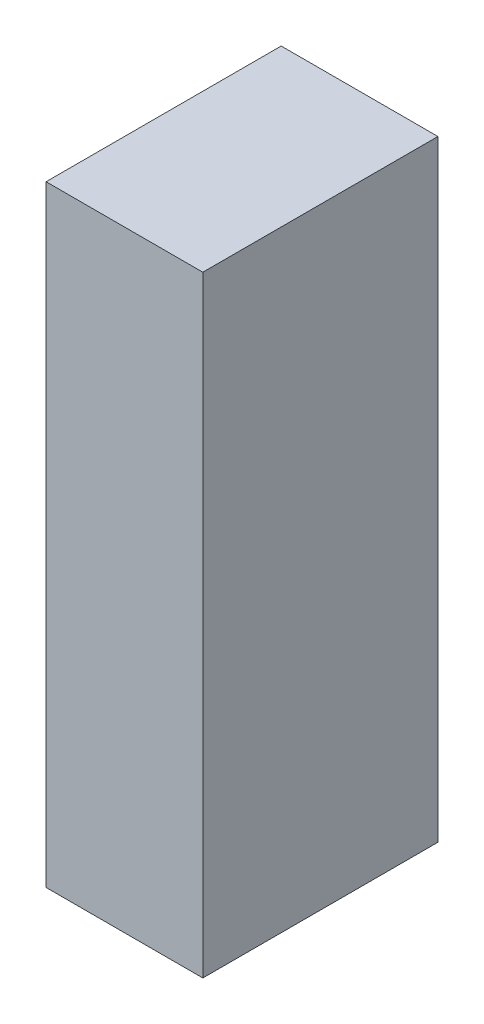
SolidWorks part; units mm, degrees
ref_plane "前视基准面" through (0, 0, 0) normal (0, 0, 1) x (1, 0, 0)
ref_plane "上视基准面" through (0, 0, 0) normal (0, 1, 0) x (1, 0, 0)
ref_plane "右视基准面" through (0, 0, 0) normal (1, 0, 0) x (0, 0, -1)
other "Configuration Table"
sketch "草图1" plane through (-22.1246, 0, -6.0743) normal (1, 0, 0) x (0, 0, -1)
  line L0 (-52, -97) -> (-10, -97) construction
  line L1 (-46, -97) -> (-31, -97)
  line L2 (-46, -97) -> (-46, -58)
  line L3 (-46, -58) -> (-31, -58)
  line L4 (-31, -97) -> (-31, -58)
  line L5 (-40, -58) -> (-10, -58) construction
  point P8 (0, 0)
  point P11 (0, 0)
  point P12 (0, 0)
  dimension "D1" = 15
extrude "凸台-拉伸1" add sketch "草图1" along normal mid plane 10
